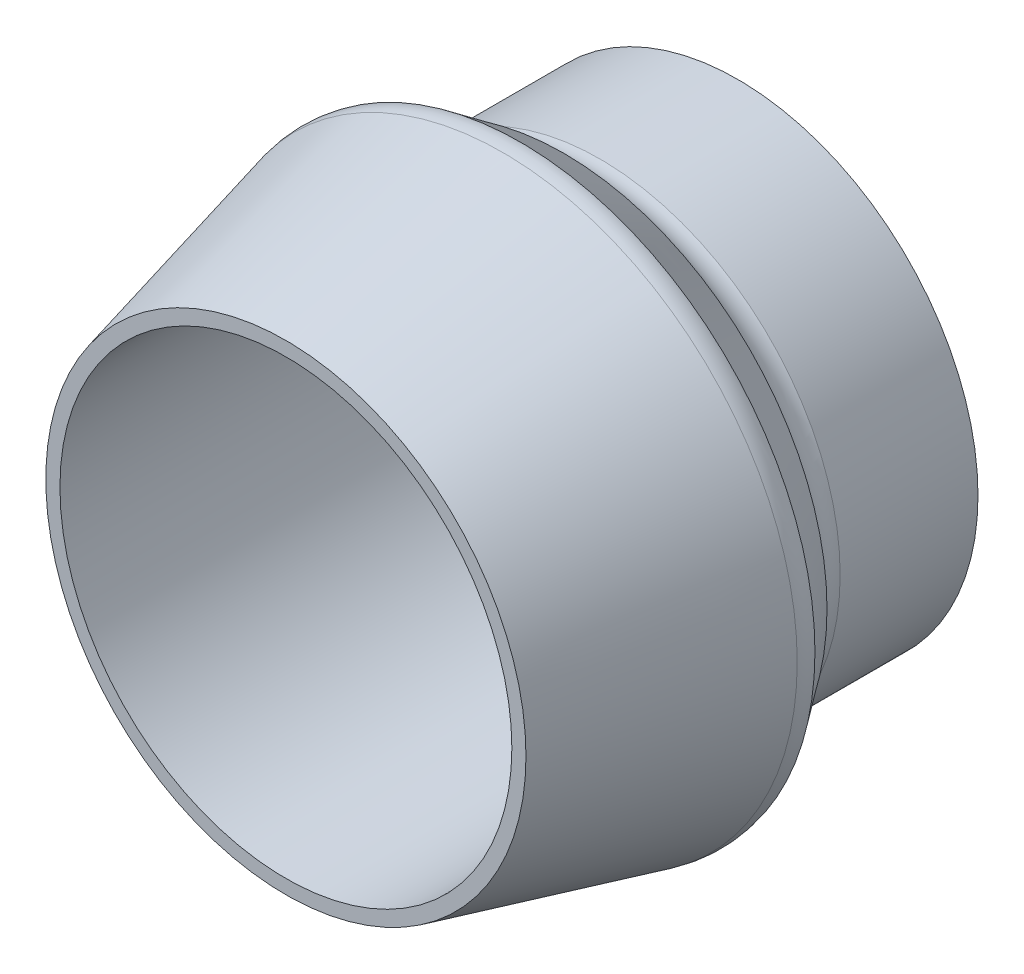
SolidWorks part; units mm, degrees
ref_plane "Plano frontal" through (0, 0, 0) normal (0, 0, 1) x (1, 0, 0)
ref_plane "Plano superior" through (0, 0, 0) normal (0, 1, 0) x (1, 0, 0)
ref_plane "Plano direito" through (0, 0, 0) normal (1, 0, 0) x (0, 0, -1)
sketch "Esboço1" plane through (0, 0, 0) normal (1, 0, 0) x (0, 0, -1)
  line L0 (-35, 3.675) -> (-39.2753, 3.7546) construction
  line L1 (-36.6996, 4.1334) -> (-36.0922, 3.6953)
  line L3 (-40, 3.175) -> (-33.65, 3.175) construction
  line L10 (-40, 0) -> (-33.65, 0) construction
  line L11 (-33.65, 3.175) -> (-40, 3.175)
  line L18 (-40, 3.175) -> (-40, 3.3734)
  line L19 (-40, 3.3734) -> (-36.951, 4.1357)
  line L23 (-35.5866, 3.3746) -> (-33.65, 3.3746)
  line L24 (-33.65, 3.3746) -> (-33.65, 3.175)
  line L25 (-33.65, 3.175) -> (-33.6458, 3.1746)
  arc A0 (-36.0922, 3.6953) -> (-35.5866, 3.3746) centre (-35.679, 3.7877) ccw
  arc A1 (-36.6996, 4.1334) -> (-36.951, 4.1357) centre (-36.8298, 3.6506) ccw
  point P0 (-1.35, 0)
  point P11 (-36.825, 0)
  dimension "D7" = 0.5
  dimension "D1" = 6.35
revolve "Revolução4" add sketch "Esboço1" angle 360 about L10
